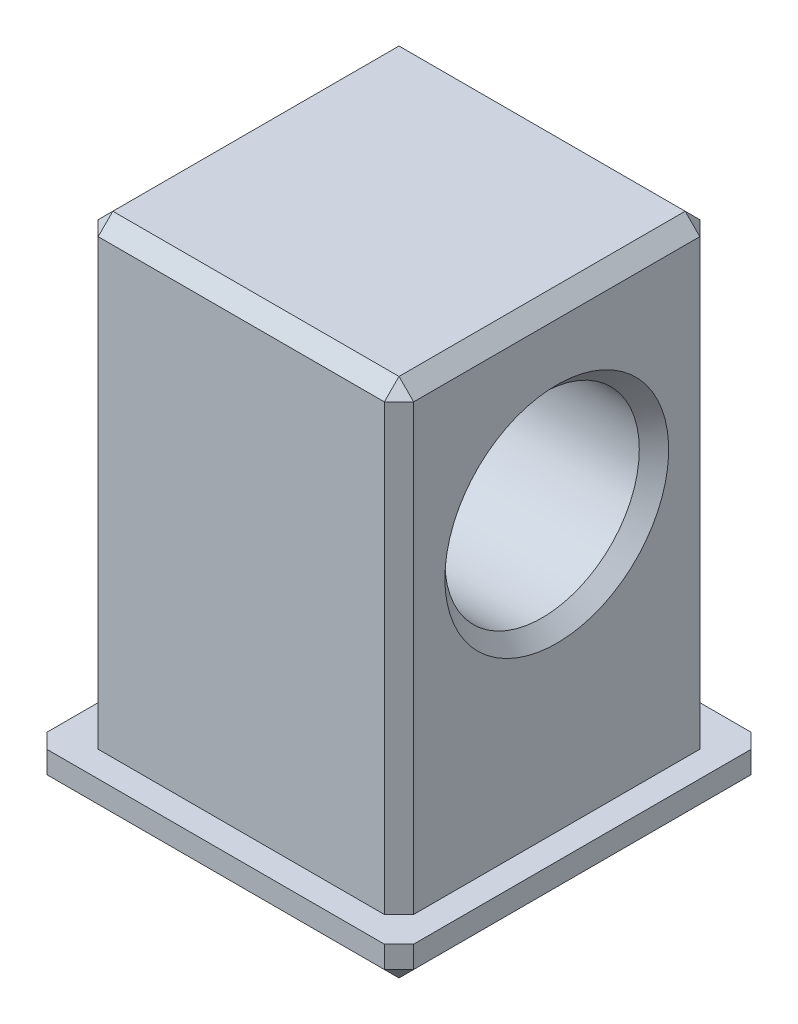
SolidWorks part; units mm, degrees
ref_plane "Front Plane" through (0, 0, 0) normal (0, 0, 1) x (1, 0, 0)
ref_plane "Top Plane" through (0, 0, 0) normal (0, 1, 0) x (1, 0, 0)
ref_plane "Right Plane" through (0, 0, 0) normal (1, 0, 0) x (0, 0, -1)
sketch "Sketch1" plane through (0, 0, 0) normal (0, 1, 0) x (1, 0, 0)
  line L1 (0, 0) -> (25.4, 0)
  line L2 (0, 0) -> (0, 25.4)
  line L3 (0, 25.4) -> (25.4, 25.4)
  line L4 (25.4, 0) -> (25.4, 25.4)
  dimension "D1" = 25.4
extrude "Boss-Extrude1" add sketch "Sketch1" along normal blind 2.54
sketch "Sketch2" plane through (0, 2.54, 0) normal (0, 1, 0) x (1, 0, 0)
  line L0 (0, 12.7) -> (25.4, 12.7) construction
  line L1 (1.778, 1.778) -> (23.622, 1.778)
  line L2 (1.778, 1.778) -> (1.778, 23.622)
  line L3 (1.778, 23.622) -> (23.622, 23.622)
  line L4 (23.622, 1.778) -> (23.622, 23.622)
  line L5 (0, 25.4) -> (0, 0) construction
  line L6 (25.4, 0) -> (25.4, 25.4) construction
  line L7 (12.7, 25.4) -> (12.7, 0) construction
  line L8 (25.4, 25.4) -> (0, 25.4) construction
  line L9 (0, 0) -> (25.4, 0) construction
  point P10 (1.778, 12.7)
  point P17 (12.7, 23.622)
  dimension "D1" = 21.844
extrude "Boss-Extrude2" add sketch "Sketch2" along normal blind 31.75
sketch "Sketch3" plane through (1.778, 0, 0) normal (-1, 0, 0) x (0, 0, 1)
  line L0 (-12.7, 34.29) -> (-12.7, 2.54) construction
  line L1 (-23.622, 2.54) -> (-1.778, 2.54) construction
  line L2 (-23.622, 34.29) -> (-1.778, 34.29) construction
  circle A0 centre (-12.7, 21.59) radius 6.731
  point P8 (0, 0)
  dimension "D1" = 13.462
  dimension "D2" = 19.05
extrude "Cut-Extrude1" cut sketch "Sketch3" against normal through all
chamfer "Chamfer1" distance 1.016 angle 45 18 edges at (1.778, 21.59, -5.969) (23.622, 21.59, -5.969) (1.778, 18.415, -23.622) (12.7, 34.29, -23.622) (1.778, 34.29, -12.7) (1.778, 18.415, -1.778) (12.7, 34.29, -1.778) (23.622, 18.415, -1.778) (23.622, 34.29, -12.7) (23.622, 18.415, -23.622) (25.4, 1.27, -25.4) (25.4, 1.27, 0) (12.7, 0, 0) (25.4, 0, -12.7) (0, 1.27, -25.4) (12.7, 0, -25.4) (0, 0, -12.7) (0, 1.27, 0)
